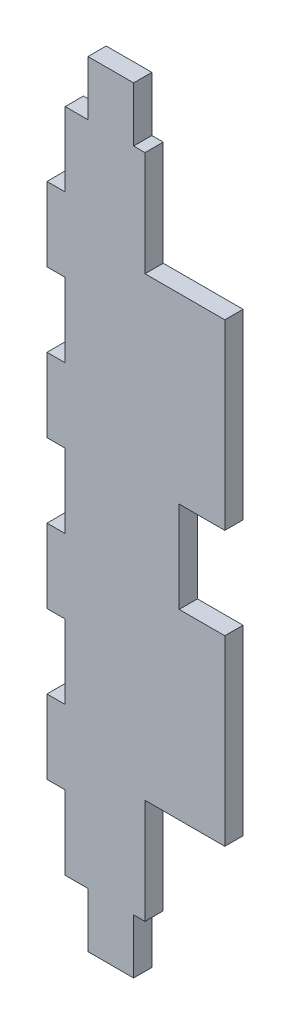
SolidWorks part; units mm, degrees
material "Beech"
ref_plane "Front Plane" through (0, 0, 0) normal (0, 0, 1) x (1, 0, 0)
ref_plane "Top Plane" through (0, 0, 0) normal (0, 1, 0) x (1, 0, 0)
ref_plane "Right Plane" through (0, 0, 0) normal (1, 0, 0) x (0, 0, -1)
sketch "Sketch1" plane through (0, 0, 0) normal (0, 0, 1) x (1, 0, 0)
  line L0 (0, 0) -> (0, -20.6022)
  line L1 (0, -20.6022) -> (-5.08, -20.6022)
  line L2 (-5.08, -20.6022) -> (-5.08, -41.2044)
  line L3 (-5.08, -41.2044) -> (0, -41.2044)
  line L4 (0, -41.2044) -> (0, -61.8067)
  line L5 (0, -61.8067) -> (-5.08, -61.8067)
  line L6 (-5.08, -61.8067) -> (-5.08, -82.4089)
  line L7 (-5.08, -82.4089) -> (0, -82.4089)
  line L8 (0, -82.4089) -> (0, -103.0111)
  line L9 (0, -103.0111) -> (-5.08, -103.0111)
  line L10 (-5.08, -103.0111) -> (-5.08, -123.6133)
  line L11 (-5.08, -123.6133) -> (0, -123.6133)
  line L12 (0, -123.6133) -> (0, -144.2156)
  line L13 (0, -144.2156) -> (-5.08, -144.2156)
  line L14 (-5.08, -144.2156) -> (-5.08, -164.8178)
  line L15 (-5.08, -164.8178) -> (0, -164.8178)
  line L16 (0, -164.8178) -> (0, -185.42)
  line L17 (0, -185.42) -> (6.35, -185.42)
  line L18 (6.35, -185.42) -> (6.35, -200.66)
  line L19 (6.35, -200.66) -> (19.05, -200.66)
  line L20 (19.05, -200.66) -> (19.05, -185.42)
  line L21 (19.05, -185.42) -> (22.225, -185.42)
  line L22 (22.225, -185.42) -> (22.225, -156.21)
  line L23 (22.225, -156.21) -> (44.45, -156.21)
  line L24 (44.45, -156.21) -> (44.45, -29.21)
  line L25 (44.45, -29.21) -> (22.225, -29.21)
  line L26 (22.225, -29.21) -> (22.225, 0)
  line L27 (22.225, 0) -> (19.05, 0)
  line L28 (19.05, 0) -> (19.05, 15.24)
  line L29 (19.05, 15.24) -> (6.35, 15.24)
  line L30 (6.35, 15.24) -> (6.35, 0)
  line L31 (6.35, 0) -> (0, 0)
  point P32 (0, 0)
  dimension "D1" = 185.42
  dimension "D2" = 5.08
  dimension "D3" = 15.24
  dimension "D4" = 15.24
  dimension "D5" = 6.35
  dimension "D6" = 12.7
  dimension "D7" = 3.175
  dimension "D8" = 22.225
  dimension "D9" = 127
extrude "Boss-Extrude1" add sketch "Sketch1" along normal blind 5.08
sketch "Sketch2" plane through (0, 0, 5.08) normal (0, 0, 1) x (1, 0, 0)
  line L0 (44.45, -156.21) -> (44.45, -29.21) construction
  line L1 (31.75, -105.41) -> (57.15, -105.41)
  line L2 (31.75, -105.41) -> (31.75, -80.01)
  line L3 (31.75, -80.01) -> (57.15, -80.01)
  line L4 (57.15, -105.41) -> (57.15, -80.01)
  line L5 (31.75, -105.41) -> (57.15, -80.01) construction
  line L6 (31.75, -80.01) -> (57.15, -105.41) construction
  point P0 (44.45, -92.71)
  dimension "D1" = 25.4
  dimension "D2" = 25.4
extrude "Cut-Extrude1" cut sketch "Sketch2" against normal through all contours L4 L3 L2 L1
